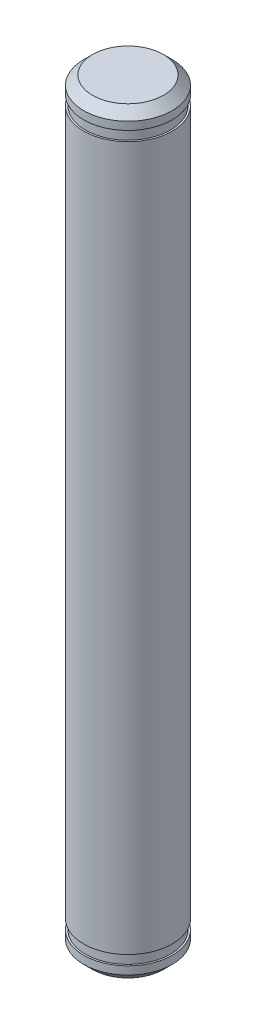
SolidWorks part; units mm, degrees
ref_plane "前视基准面" through (0, 0, 0) normal (0, 0, 1) x (1, 0, 0)
ref_plane "上视基准面" through (0, 0, 0) normal (0, 1, 0) x (1, 0, 0)
ref_plane "右视基准面" through (0, 0, 0) normal (1, 0, 0) x (0, 0, -1)
other "Configuration Table"
sketch "草图1" plane through (0, 0, 0) normal (0, 0, 1) x (1, 0, 0)
  line L0 (0, 61.8249) -> (0, -44.5084) construction
  line L1 (0, 42.75) -> (5, 42.75)
  line L2 (5, 42.75) -> (5, 29.0012)
  line L6 (5, -29.0012) -> (5, -42.75)
  line L7 (5, -42.75) -> (0, -42.75)
  line L8 (0, 0) -> (41.6667, 0) construction
  line L9 (0, 42.75) -> (0, -42.75)
  line L10 (5, 29.0012) -> (5, -29.0012)
  dimension "D1" = 5
  dimension "D2" = 5
  dimension "D5" = 85.5
revolve "旋转1" add sketch "草图1" angle 360 about L9
chamfer "倒角1" distance 1 angle 45 2 edges at (0, -42.75, 5) (0, 42.75, 5)
ref_plane "基准面1" through (0, 0, 0) normal (0, 1, 0) x (1, 0, 0)
sketch "草图2" plane through (0, 42.75, 0) normal (0, 1, 0) x (1, 0, 0)
  circle A0 centre (0, 0) radius 5 construction
  circle A1 centre (0, 0) radius 5
  circle A2 centre (0, 0) radius 4.8
  dimension "D1" = 9.6
extrude "切除-拉伸1" cut sketch "草图2" along normal blind 1.1 from offset 3 offset against normal yes
mirror "镜向1" about plane through (0, 0, 0) normal (0, 1, 0) of "切除-拉伸1"
